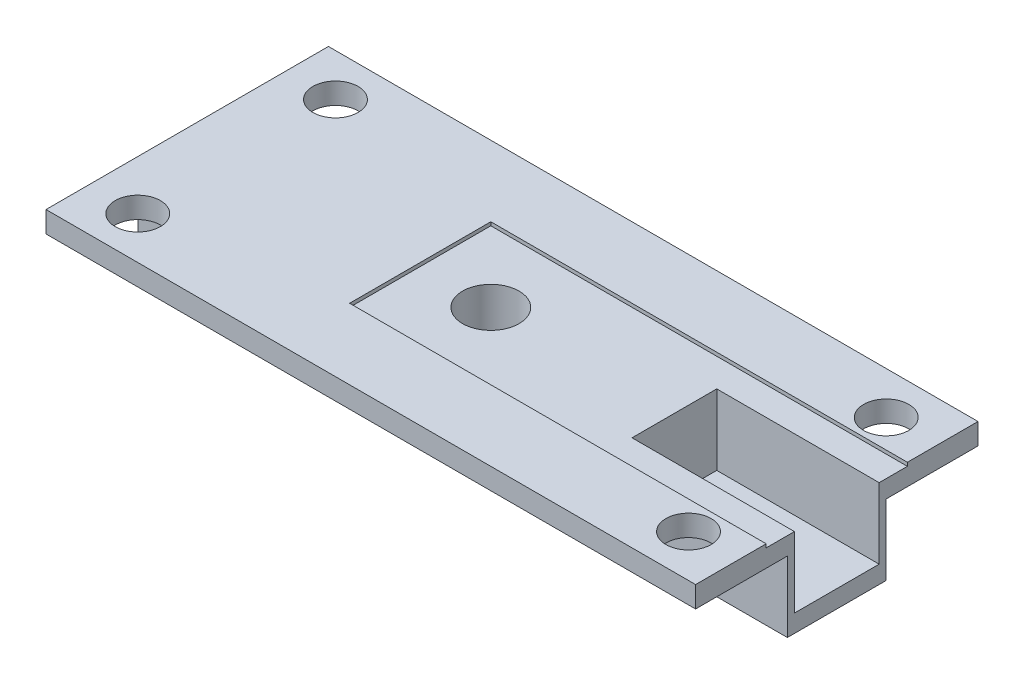
SolidWorks part; units mm, degrees
ref_plane "前视基准面" through (0, 0, 0) normal (0, 0, 1) x (1, 0, 0)
ref_plane "上视基准面" through (0, 0, 0) normal (0, 1, 0) x (1, 0, 0)
ref_plane "右视基准面" through (0, 0, 0) normal (1, 0, 0) x (0, 0, -1)
sketch "草图1" plane through (0, 0, 0) normal (0, 1, 0) x (1, 0, 0)
  line L0 (0, 0) -> (77.6298, 0) construction
  line L1 (0, 0) -> (0, 52.5196) construction
  line L3 (-23, 10) -> (23, 10)
  line L4 (-23, 10) -> (-23, -10)
  line L5 (-23, -10) -> (23, -10)
  line L6 (23, 10) -> (23, -10)
  circle A0 centre (-19.5, 7) radius 1.6
  circle A1 centre (19.5, 7) radius 1.6
  circle A2 centre (-19.5, -7) radius 1.6
  circle A3 centre (19.5, -7) radius 1.6
  dimension "D1" = 3.2
  dimension "D2" = 7
  dimension "D3" = 19.5
  dimension "D4" = 46
  dimension "D5" = 20
extrude "凸台-拉伸1" add sketch "草图1" along normal blind 6.5
sketch "草图2" plane through (0, 6.5, 0) normal (0, 1, 0) x (1, 0, 0)
  line L0 (-6.5, 5) -> (23, 5)
  line L1 (23, -10) -> (23, 10) construction
  line L2 (-6.5, 5) -> (-6.5, -5)
  line L3 (-6.5, -5) -> (23, -5)
  line L6 (0, 0) -> (26.1999, 0) construction
  line L7 (23, 5) -> (23, -5)
  line L8 (23, 10) -> (-23, 10) construction
  line L9 (-23, -10) -> (23, -10) construction
  dimension "D1" = 10
  dimension "D2" = 5
  dimension "D3" = 29.5
extrude "切除-拉伸1" cut sketch "草图2" against normal blind 0.25
sketch "草图3" plane through (0, 6.25, 0) normal (0, 1, 0) x (1, 0, 0)
  line L0 (-6.5, 5) -> (-6.5, -5) construction
  line L4 (-6.5, -5) -> (23, -5) construction
  circle A0 centre (-1.5, 0) radius 2
  dimension "D1" = 4
  dimension "D2" = 5
  dimension "D3" = 5
extrude "切除-拉伸2" cut sketch "草图3" against normal blind 5.3
sketch "草图4" plane through (0, 0.95, 0) normal (0, 1, 0) x (1, 0, 0)
  circle A0 centre (-1.5, 0) radius 1.35
  dimension "D1" = 2.7
extrude "切除-拉伸3" cut sketch "草图4" against normal blind 1
sketch "草图5" plane through (0, 6.25, 0) normal (0, 1, 0) x (1, 0, 0)
  line L0 (11.5, 3) -> (11.5, -3)
  line L1 (-6.5, 5) -> (-6.5, -5) construction
  line L4 (23, 3) -> (23, -3)
  line L5 (23, -5) -> (23, 5) construction
  line L6 (23, 5) -> (-6.5, 5) construction
  line L7 (-6.5, -5) -> (23, -5) construction
  line L8 (11.5, 3) -> (23, 3)
  line L9 (11.5, -3) -> (23, -3)
  dimension "D1" = 18
  dimension "D2" = 6
  dimension "D3" = 2
  dimension "D4" = 2
  dimension "D5" = 11.5
  dimension "D6" = 6
extrude "切除-拉伸4" cut sketch "草图5" against normal blind 5
sketch "草图6" plane through (0, 0, 0) normal (0, -1, 0) x (1, 0, 0)
  line L0 (-23, 3) -> (23, 3)
  line L1 (-23, -10) -> (-23, 10) construction
  line L2 (23, 10) -> (23, -10) construction
  line L3 (23, 3) -> (23, -3)
  line L4 (23, -3) -> (-23, -3)
  line L5 (-23, -3) -> (-23, 3)
  line L6 (23, -10) -> (-23, -10) construction
  line L7 (-23, 10) -> (23, 10) construction
  circle A0 centre (19.5, 7) radius 1.6 construction
  circle A1 centre (-19.5, 7) radius 1.6 construction
  circle A2 centre (-19.5, -7) radius 1.6 construction
  circle A3 centre (19.5, -7) radius 1.6 construction
  circle A4 centre (-19.5, 7) radius 1.6
  circle A5 centre (-19.5, -7) radius 1.6
  circle A6 centre (19.5, -7) radius 1.6
  circle A7 centre (19.5, 7) radius 1.6
  dimension "D1" = 6
  dimension "D2" = 7
  dimension "D3" = 7
sketch "草图7" plane through (23, 0, 0) normal (1, 0, 0) x (0, 0, -1)
  line L2 (-10, 5) -> (-3.5, 5)
  line L3 (-10, 6.5) -> (-10, 0) construction
  line L8 (-3.5, 5) -> (-3.5, 0)
  line L9 (-10, 0) -> (10, 0) construction
  line L10 (-3.5, 0) -> (-10, 0)
  line L11 (-10, 0) -> (-10, 5)
  line L12 (-10, 6.5) -> (-5, 6.5) construction
  line L13 (-3, 1.25) -> (-3, 6.25) construction
  line L14 (5, 6.5) -> (10, 6.5) construction
  line L15 (10, 0) -> (3.5, 0)
  line L16 (10, 0) -> (10, 5)
  line L17 (10, 5) -> (3.5, 5)
  line L18 (3.5, 0) -> (3.5, 5)
  line L19 (3, 1.25) -> (3, 6.25) construction
  dimension "D1" = 5
  dimension "D2" = 1.5
  dimension "D3" = 0.5
  dimension "D4" = 5
  dimension "D5" = 1.5
  dimension "D6" = 0.5
extrude "切除-拉伸5" cut sketch "草图7" against normal through all
